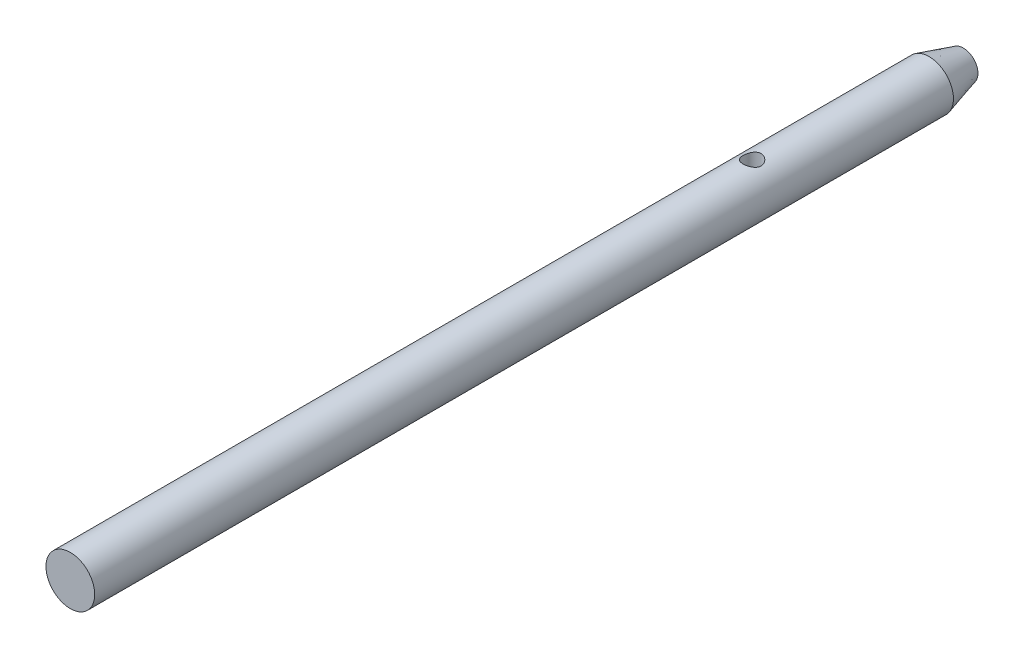
SolidWorks part; units mm, degrees
ref_plane "Plane1" through (0, 0, 0) normal (0, 0, 1) x (1, 0, 0)
ref_plane "Plane2" through (0, 0, 0) normal (0, 1, 0) x (1, 0, 0)
ref_plane "Plane3" through (0, 0, 0) normal (1, 0, 0) x (0, 0, -1)
sketch "Sketch1" plane through (0, 0, 0) normal (0, 0, 1) x (1, 0, 0)
  circle A0 centre (0, 0) radius 2.135
  dimension "D1" = 4.27
extrude "drive shaft shape" add sketch "Sketch1" along normal blind 78.2
cosmetic thread "Cosmetic Thread1" parameters "D1"=6.5, "D2"=3
chamfer "drive shaft chamfer" distance 0.85 distance2 3 1 edges at (2.135, 0, 0)
sketch "Sketch2" plane through (0, 0, 0) normal (0, 1, 0) x (1, 0, 0)
  line L0 (0, 0) -> (0, -88.6602) construction
  line L1 (0, -78.2) -> (0, -3) construction
  circle A0 centre (0, -18.5) radius 0.79
  dimension "D2" = 1.58
  dimension "D1" = 18.5
extrude "drive shaft pin hole" cut sketch "Sketch2" against normal up to next and the other way up to next
